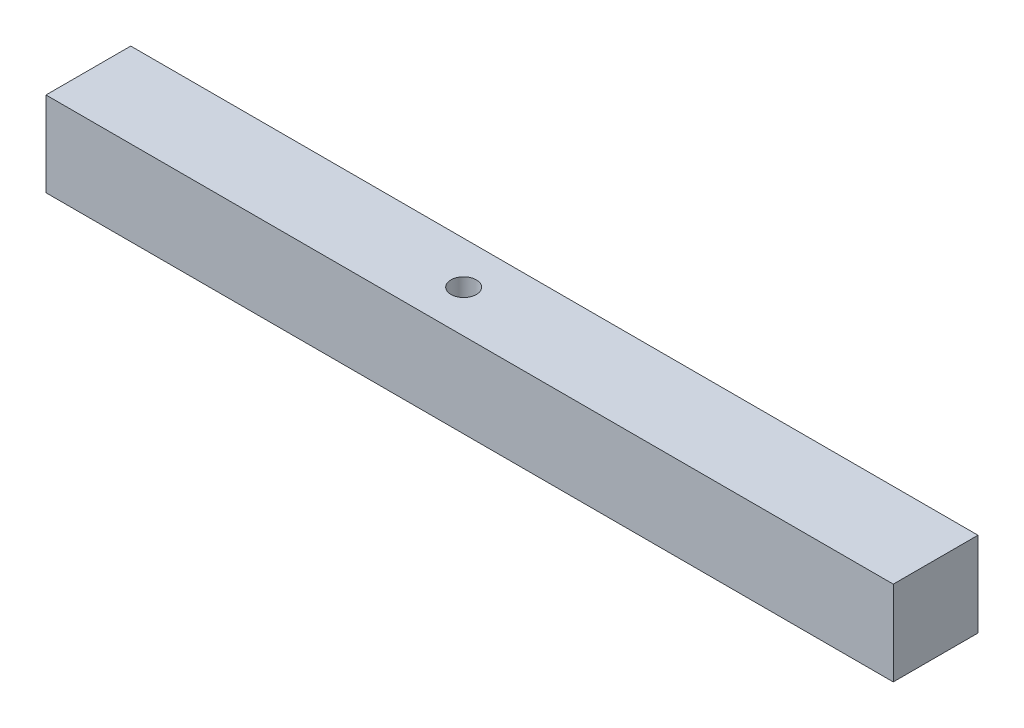
SolidWorks part; units mm, degrees
ref_plane "Front" through (0, 0, 0) normal (0, 0, 1) x (1, 0, 0)
ref_plane "Top" through (0, 0, 0) normal (0, 1, 0) x (1, 0, 0)
ref_plane "Right" through (0, 0, 0) normal (1, 0, 0) x (0, 0, -1)
sketch "Skizze1" plane through (0, 0, 0) normal (1, 0, 0) x (0, 0, -1)
  line L1 (-10, -10) -> (10, -10)
  line L2 (-10, -10) -> (-10, 10)
  line L3 (-10, 10) -> (10, 10)
  line L4 (10, -10) -> (10, 10)
  line L5 (-10, -10) -> (10, 10) construction
  line L6 (-10, 10) -> (10, -10) construction
  point P0 (0, 0)
  dimension "D1" = 20
extrude "Aufsatz-Linear austragen1" add sketch "Skizze1" along normal blind 200
sketch "Skizze2" plane through (0, 10, 0) normal (0, 1, 0) x (1, 0, 0)
  line L0 (0, 0) -> (200, 0) construction
  line L1 (0, 10) -> (0, -10) construction
  line L2 (200, 10) -> (200, -10) construction
  line L3 (100, 0) -> (100, 10) construction
  line L4 (200, 10) -> (0, 10) construction
  circle A0 centre (88.59, 0) radius 3
  circle A1 centre (111.41, 0) radius 3 construction
  dimension "D2" = 6
  dimension "D1" = 88.59
extrude "Schnitt-Linear austragen1" cut sketch "Skizze2" against normal through all
